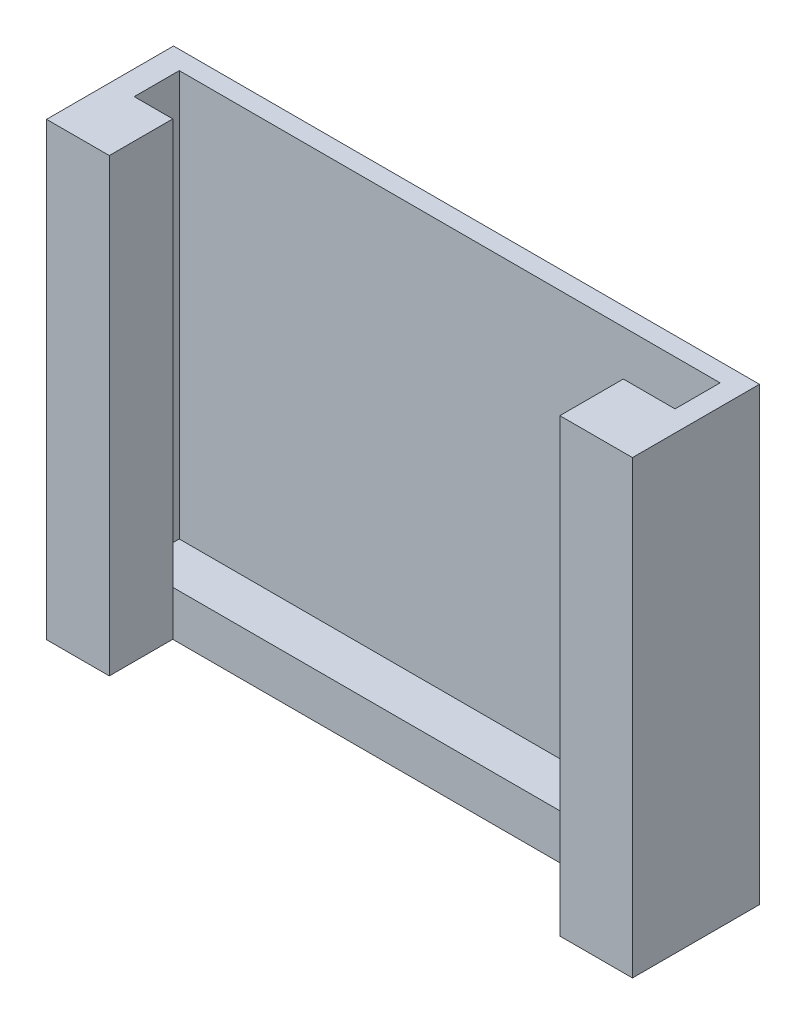
SolidWorks part; units mm, degrees
ref_plane "Front Plane" through (0, 0, 0) normal (0, 0, 1) x (1, 0, 0)
ref_plane "Top Plane" through (0, 0, 0) normal (0, 1, 0) x (1, 0, 0)
ref_plane "Right Plane" through (0, 0, 0) normal (1, 0, 0) x (0, 0, -1)
sketch "Sketch1" plane through (0, 0, 0) normal (0, 1, 0) x (1, 0, 0)
  line L1 (6.5, -14) -> (-6.5, -14)
  line L2 (6.5, -14) -> (6.5, 14)
  line L3 (6.5, 14) -> (-6.5, 14)
  line L4 (-6.5, -14) -> (-6.5, 14)
  line L5 (6.5, -14) -> (-6.5, 14) construction
  line L6 (6.5, 14) -> (-6.5, -14) construction
  point P0 (0, 0)
extrude "Boss-Extrude1" add sketch "Sketch1" along normal blind 10
sketch "Sketch2" plane through (0, 10, 0) normal (0, 1, 0) x (1, 0, 0)
  line L1 (0, 13.5906) -> (-5.9635, 13.5906)
  line L2 (0, 13.5906) -> (6.0365, 13.5906)
  line L3 (6.0365, 13.5906) -> (6.0365, 12.5906)
  line L4 (6.0365, 12.5906) -> (-5.9635, 12.5906)
  line L5 (-5.9635, 12.5906) -> (-5.9635, 13.5906)
extrude "Cut-Extrude1" cut sketch "Sketch2" against normal blind 9
sketch "Sketch3" plane through (0, 10, 0) normal (0, 1, 0) x (1, 0, 0)
  line L10 (-5.1079, 12.5906) -> (-5.1079, 11.1826)
  line L11 (-5.9635, 12.5906) -> (6.0365, 12.5906) construction
  line L12 (-5.1079, 11.1826) -> (-6.5, 11.1826)
  line L13 (-6.5, 14) -> (-6.5, -14) construction
  line L14 (-6.5, 11.1826) -> (-6.5, -14)
  line L15 (-6.5, -14) -> (6.5, -14)
  line L16 (6.5, -14) -> (6.5, 11.1826)
  line L17 (6.5, -14) -> (6.5, 14) construction
  line L18 (6.5, 11.1826) -> (4.889, 11.1826)
  line L19 (4.889, 11.1826) -> (4.889, 12.5906)
  line L20 (4.889, 12.5906) -> (-5.1079, 12.5906)
extrude "Cut-Extrude3" cut sketch "Sketch3" against normal through all
